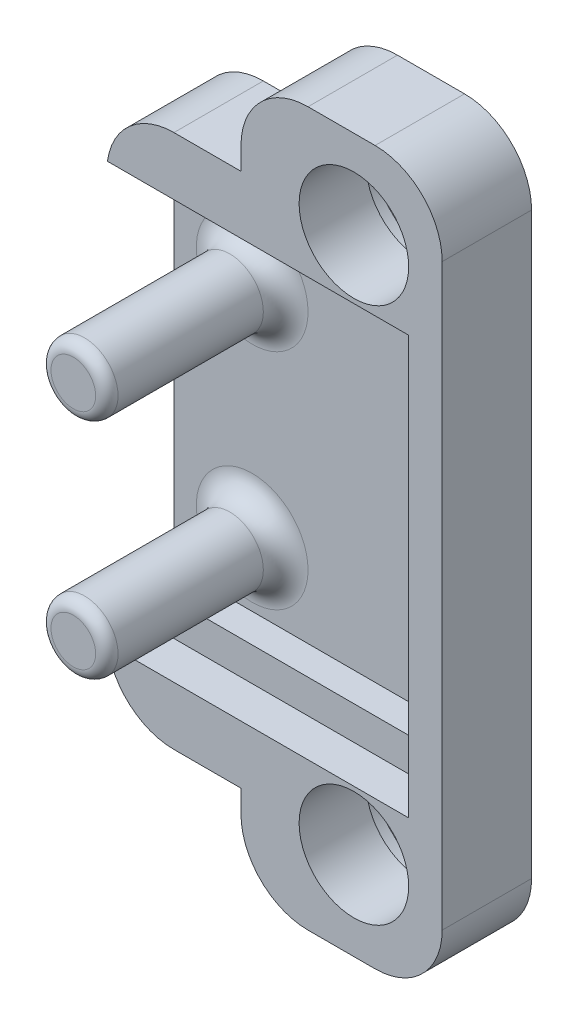
SolidWorks part; units mm, degrees
ref_plane "Front Plane" through (0, 0, 0) normal (0, 0, 1) x (1, 0, 0)
ref_plane "Top Plane" through (0, 0, 0) normal (0, 1, 0) x (1, 0, 0)
ref_plane "Right Plane" through (0, 0, 0) normal (1, 0, 0) x (0, 0, -1)
sketch "Sketch1" plane through (0, 0, 0) normal (0, 0, 1) x (1, 0, 0)
  line L0 (-10.2404, 15.95) -> (-10.2404, -15.95)
  line L1 (-6.2904, -12) -> (6.2904, -12)
  line L2 (-6.2904, -12) -> (-6.2904, 12)
  line L3 (-6.2904, 12) -> (6.2904, 12)
  line L4 (6.2904, -12) -> (6.2904, 12)
  line L5 (-6.2904, -12) -> (6.2904, 12) construction
  line L6 (-6.2904, 12) -> (6.2904, -12) construction
  line L7 (-8.7404, 14.45) -> (8.7404, 14.45)
  line L8 (-8.7404, 14.45) -> (-8.7404, -14.45)
  line L9 (-8.7404, -14.45) -> (8.7404, -14.45)
  line L10 (8.7404, 14.45) -> (8.7404, -14.45)
  line L11 (-8.7404, 14.45) -> (8.7404, -14.45) construction
  line L12 (-8.7404, -14.45) -> (8.7404, 14.45) construction
  line L13 (-10.2404, -15.95) -> (10.2404, -15.95)
  line L14 (10.2404, 15.95) -> (10.2404, -15.95)
  line L15 (-10.2404, 15.95) -> (10.2404, 15.95)
  circle A0 centre (6.2904, 12) radius 2.45
  circle A1 centre (6.2904, -12) radius 2.45
  point P0 (0, 0)
  point P8 (0, 0)
  dimension "D2" = 4.9
  dimension "D3" = 4.9
  dimension "D1" = 24
  dimension "D5" = 31.9
  dimension "D4" = 1.5
extrude "Boss-Extrude1" add sketch "Sketch1" along normal blind 4 contours L15 L0 L13 L14 L7 L10 L9 L8 | A0 L10 L7 | A1 L1 L2 L3 A0 L7 L8 L9 | A1 L10 A0 L4 | A1 L4 A0 L3 L2 L1 | A1 L9 L10
sketch "Sketch2" plane through (0, 0, 4) normal (0, 0, 1) x (1, 0, 0)
  line L0 (10.2404, 15.95) -> (8.7404, 15.95)
  line L1 (-10.2404, 15.95) -> (10.2404, 15.95) construction
  line L2 (8.7404, 15.95) -> (8.7404, -15.95)
  line L3 (-10.2404, -15.95) -> (10.2404, -15.95) construction
  line L4 (8.7404, 0) -> (-10.2404, 0)
  line L5 (-10.2404, 15.95) -> (-10.2404, -15.95) construction
  line L7 (-10.2404, -9.35) -> (8.7404, -9.35)
  line L8 (-10.2404, -9.35) -> (-10.2404, 9.35)
  line L9 (-10.2404, 9.35) -> (8.7404, 9.35)
  line L10 (8.7404, -9.35) -> (8.7404, 9.35)
  line L11 (-10.2404, -9.35) -> (8.7404, 9.35) construction
  line L12 (-10.2404, 9.35) -> (8.7404, -9.35) construction
  point P12 (-0.75, 0)
  line M11 (-10.2404, 15.95) -> (-10.2404, -15.95)
  dimension "D1" = 1.5
  dimension "D2" = 18.7
extrude "Cut-Extrude1" cut sketch "Sketch2" against normal blind 3 contours L9 L4 L2 M11 | L7 L2 L4 M11
sketch "Sketch3" plane through (0, 0, 1) normal (0, 0, 1) x (1, 0, 0)
  line L0 (10.2404, 0) -> (-1.2596, 0)
  line L1 (10.2404, 15.95) -> (10.2404, -15.95) construction
  line L2 (-1.2596, -5) -> (-1.2596, 5)
  circle A0 centre (-1.2596, 5) radius 1.5
  circle A1 centre (-1.2596, -5) radius 1.5
  point P7 (-1.2596, 0)
  dimension "D3" = 3
  dimension "D4" = 3
  dimension "D1" = 10
  dimension "D2" = 11.5
extrude "Boss-Extrude2" add sketch "Sketch3" along normal blind 8
sketch "Sketch4" plane through (0, 0, 1) normal (0, 0, 1) x (1, 0, 0)
  line L0 (-10.2404, 9.35) -> (-10.2404, -9.35) construction
  line L1 (8.7404, 9.35) -> (-10.2404, 9.35)
  line L2 (8.7404, 9.35) -> (8.7404, 7.85)
  line L3 (8.7404, 7.85) -> (-10.2404, 7.85)
  line L4 (-10.2404, 9.35) -> (-10.2404, 7.85)
  line L6 (8.7404, -9.35) -> (-10.2404, -9.35)
  line L7 (8.7404, -9.35) -> (8.7404, -7.85)
  line L8 (8.7404, -7.85) -> (-10.2404, -7.85)
  line L9 (-10.2404, -9.35) -> (-10.2404, -7.85)
  dimension "D1" = 1.5
  dimension "D2" = 1.5
extrude "Boss-Extrude3" add sketch "Sketch4" along normal blind 1.3
sketch "Sketch5" plane through (0, 0, 4) normal (0, 0, 1) x (1, 0, 0)
  line L0 (10.2404, 15.95) -> (-4.7596, 15.95)
  line L1 (-10.2404, 15.95) -> (10.2404, 15.95) construction
  line L3 (-4.7596, 15.95) -> (-10.2404, 15.95)
  line L4 (-4.7596, 15.95) -> (-4.7596, -15.95)
  line L5 (-4.7596, -15.95) -> (-10.2404, -15.95)
  line L6 (-10.2404, 15.95) -> (-10.2404, -15.95)
  line M6 (-10.2404, 15.95) -> (-10.2404, 9.35)
  line M7 (-10.2404, 9.35) -> (8.7404, 9.35)
  line M13 (10.2404, 15.95) -> (-10.2404, 15.95)
  dimension "D1" = 15
extrude "Cut-Extrude2" cut sketch "Sketch5" against normal blind 7.4 contours L4 M13 M6 M7
sketch "Sketch6" plane through (0, 0, 4) normal (0, 0, 1) x (1, 0, 0)
  line L1 (-4.7596, 15.95) -> (1.2404, 15.95)
  line L2 (-4.7596, 15.95) -> (-4.7596, 11.95)
  line L3 (-4.7596, 11.95) -> (1.2404, 11.95)
  line L4 (1.2404, 15.95) -> (1.2404, 11.95)
  line L5 (-4.7596, -15.95) -> (1.2404, -15.95)
  line L6 (-4.7596, -15.95) -> (-4.7596, -11.95)
  line L7 (-4.7596, -11.95) -> (1.2404, -11.95)
  line L8 (1.2404, -15.95) -> (1.2404, -11.95)
  line M11 (10.2404, 15.95) -> (-4.7596, 15.95)
  line M12 (-4.7596, 15.95) -> (-4.7596, 9.35)
  line M16 (-4.7596, -9.35) -> (-4.7596, -15.95)
  line M17 (-4.7596, -15.95) -> (10.2404, -15.95)
  dimension "D1" = 6
  dimension "D2" = 6
  dimension "D3" = 4
  dimension "D4" = 4
extrude "Cut-Extrude3" cut sketch "Sketch6" against normal up to surface (4 mm away) contours L4 L3 M11 M12 | L8 L7 M17 M16 up to face at (8.7404, -12, 0)
fillet "Fillet1" radius 3 6 edges at (10.2404, 15.95, 2) (10.2404, -15.95, 2) (1.2404, -15.95, 2) (-4.7596, -11.95, 2) (-4.7596, 11.95, 2) (1.2404, 15.95, 2)
fillet "Fillet2" radius 1 2 edges at (0.2404, -5, 1) (0.2404, 5, 1)
fillet "Fillet3" radius 0.5 2 edges at (0.2404, -5, 9) (0.2404, 5, 9)
sketch "Sketch7" plane through (0, 0, 0) normal (0, 0, -1) x (-1, 0, 0)
  circle A0 centre (-6.2904, 12) radius 3.25
  circle A1 centre (-6.2904, -12) radius 3.25
  dimension "D1" = 6.5
  dimension "D2" = 6.5
extrude "Cut-Extrude4" cut sketch "Sketch7" against normal blind 1
